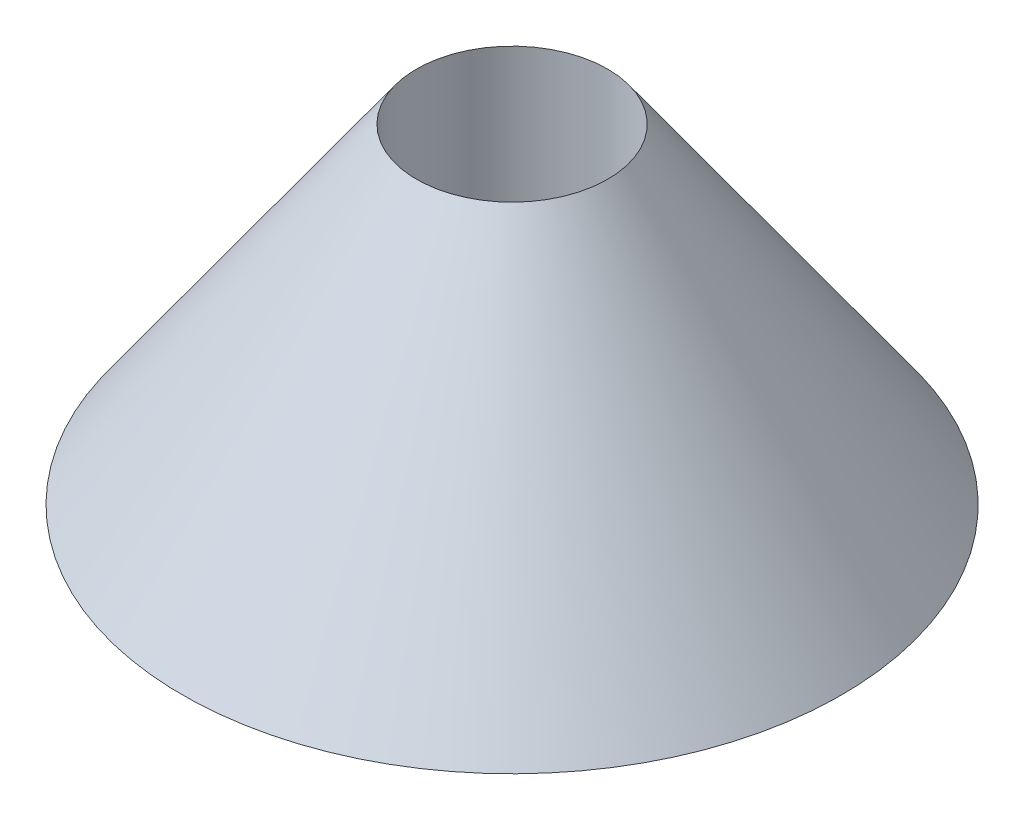
SolidWorks part; units mm, degrees
ref_plane "Alzado" through (0, 0, 0) normal (0, 0, 1) x (1, 0, 0)
ref_plane "Planta" through (0, 0, 0) normal (0, 1, 0) x (1, 0, 0)
ref_plane "Vista lateral" through (0, 0, 0) normal (1, 0, 0) x (0, 0, -1)
sketch "Croquis2" plane through (0, 0, 0) normal (0, 0, 1) x (1, 0, 0)
  line L0 (-59.9661, -10.8133) -> (-64.9661, -10.8133)
  line L1 (-59.9661, -10.8133) -> (-59.9661, -9.3133)
  line L2 (-59.9661, -9.3133) -> (-61.4161, -9.3133)
  line L3 (-61.4161, -9.3133) -> (-61.4161, -5.8133)
  line L4 (-61.4161, -5.8133) -> (-64.9661, -10.8133)
revolve "Revolución1" add sketch "Croquis2" angle 360 about L1
